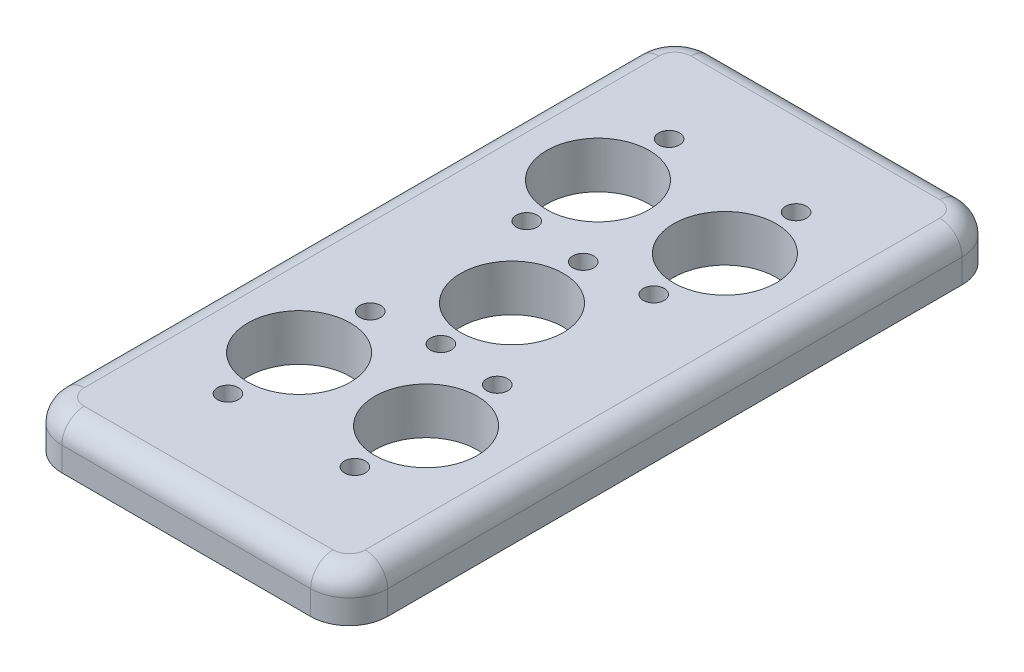
SolidWorks part; units mm, degrees
material "ABS"
ref_plane "Front Plane" through (0, 0, 0) normal (0, 0, 1) x (1, 0, 0)
ref_plane "Top Plane" through (0, 0, 0) normal (0, 1, 0) x (1, 0, 0)
ref_plane "Right Plane" through (0, 0, 0) normal (1, 0, 0) x (0, 0, -1)
sketch "Sketch1" plane through (0, 0, 0) normal (0, 1, 0) x (1, 0, 0)
  line L1 (-25.4, 50.8) -> (25.4, 50.8)
  line L2 (-25.4, 50.8) -> (-25.4, -50.8)
  line L3 (-25.4, -50.8) -> (25.4, -50.8)
  line L4 (25.4, 50.8) -> (25.4, -50.8)
  line L5 (-25.4, 50.8) -> (25.4, -50.8) construction
  line L6 (-25.4, -50.8) -> (25.4, 50.8) construction
  point P0 (0, 0)
  dimension "D1" = 101.6
  dimension "D2" = 50.8
extrude "Boss-Extrude1" add sketch "Sketch1" along normal blind 7.25
fillet "Fillet1" radius 6 4 edges at (25.4, 3.625, -50.8) (-25.4, 3.625, -50.8) (-25.4, 3.625, 50.8) (25.4, 3.625, 50.8)
fillet "Fillet2" radius 3.5 8 edges at (23.6426, 7.25, 49.0426) (0, 7.25, 50.8) (-23.6426, 7.25, 49.0426) (-25.4, 7.25, 0) (-23.6426, 7.25, -49.0426) (0, 7.25, -50.8) (23.6426, 7.25, -49.0426) (25.4, 7.25, 0)
sketch "Sketch2" plane through (0, 0, 0) normal (0, -1, 0) x (1, 0, 0)
  circle A0 centre (0, 0) radius 8
  circle A1 centre (0, 0) radius 7.5
  circle A2 centre (0, 0) radius 7.5 construction
  circle A3 centre (-9.9, 23.3) radius 7.5 construction
  circle A4 centre (9.9, 23.3) radius 7.5 construction
  circle A5 centre (9.9, -23.3) radius 7.5 construction
  circle A6 centre (-9.9, -23.3) radius 7.5 construction
  circle A7 centre (-9.9, 23.3) radius 7.5 construction
  circle A8 centre (9.9, 23.3) radius 7.5 construction
  circle A9 centre (9.9, -23.3) radius 7.5 construction
  circle A10 centre (-9.9, -23.3) radius 7.5 construction
  circle A11 centre (9.9, 23.3) radius 8
  circle A12 centre (-9.9, 23.3) radius 8
  circle A13 centre (9.9, -23.3) radius 8
  circle A14 centre (-9.9, -23.3) radius 8
  dimension "D1" = 0
  dimension "D2" = 0.5
  dimension "D3" = 0.5
extrude "Cut-Extrude1" cut sketch "Sketch2" against normal up to next
hole_wizard "#4 Clearance Hole1" positions "Sketch4" profile "Sketch3" hole size "#4" standard "Ansi Inch" end condition up to next
sketch "Sketch4" plane through (0, 7.25, 0) normal (0, 1, 0) x (-1, 0, 0)
  circle A0 centre (-9.9, 12.2) radius 1.6 construction
  point P0 (-9.9, 12.2)
  point P6 (-9.9, 34.4)
  point P9 (9.9, 34.4)
  point P12 (9.9, 12.2)
  point P15 (0, 11.1)
  point P18 (0, -11.1)
  point P21 (9.9, -12.2)
  point P24 (-9.9, -12.2)
  point P27 (9.9, -34.4)
  point P30 (-9.9, -34.4)
sketch "Sketch3" plane through (9.9, 7.25, 12.2) normal (1, 0, 0) x (0, 0, 1)
  line L0 (0, 0) -> (0, 7.25)
  line L1 (0, 7.25) -> (1.6319, 7.25)
  line L2 (1.6319, 7.25) -> (1.6319, 0)
  line L5 (1.6319, 0) -> (0, 0)
  line L11 (0, -6.35) -> (0, 107.95) construction
  dimension "Thru Hole Dia." = 3.2639
  dimension "Thru Hole Depth" = 7.25
